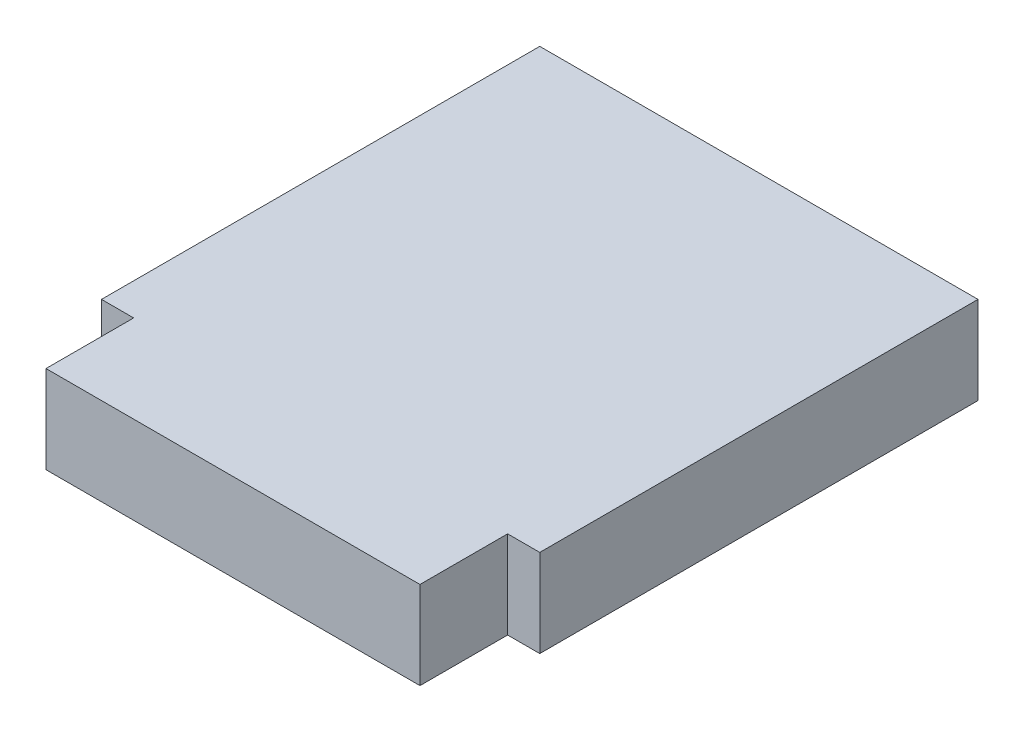
SolidWorks part; units mm, degrees
material "Acrylic (Medium-high impact)"
ref_plane "Front Plane" through (0, 0, 0) normal (0, 0, 1) x (1, 0, 0)
ref_plane "Top Plane" through (0, 0, 0) normal (0, 1, 0) x (1, 0, 0)
ref_plane "Right Plane" through (0, 0, 0) normal (1, 0, 0) x (0, 0, -1)
sketch "Sketch1" plane through (0, 0, 0) normal (0, 1, 0) x (1, 0, 0)
  line L0 (12.8, 3) -> (13.9, 3)
  line L1 (0, 0) -> (12.8, 0)
  line L2 (0, 0) -> (0, 3)
  line L4 (12.8, 0) -> (12.8, 3)
  line L5 (13.9, 3) -> (13.9, 18)
  line L6 (13.9, 18) -> (-1.1, 18)
  line L7 (-1.1, 18) -> (-1.1, 3)
  line L8 (-1.1, 3) -> (0, 3)
  dimension "D1" = 12.8
  dimension "D2" = 3
  dimension "D3" = 15
  dimension "D4" = 15
extrude "Boss-Extrude1" add sketch "Sketch1" along normal blind 3
